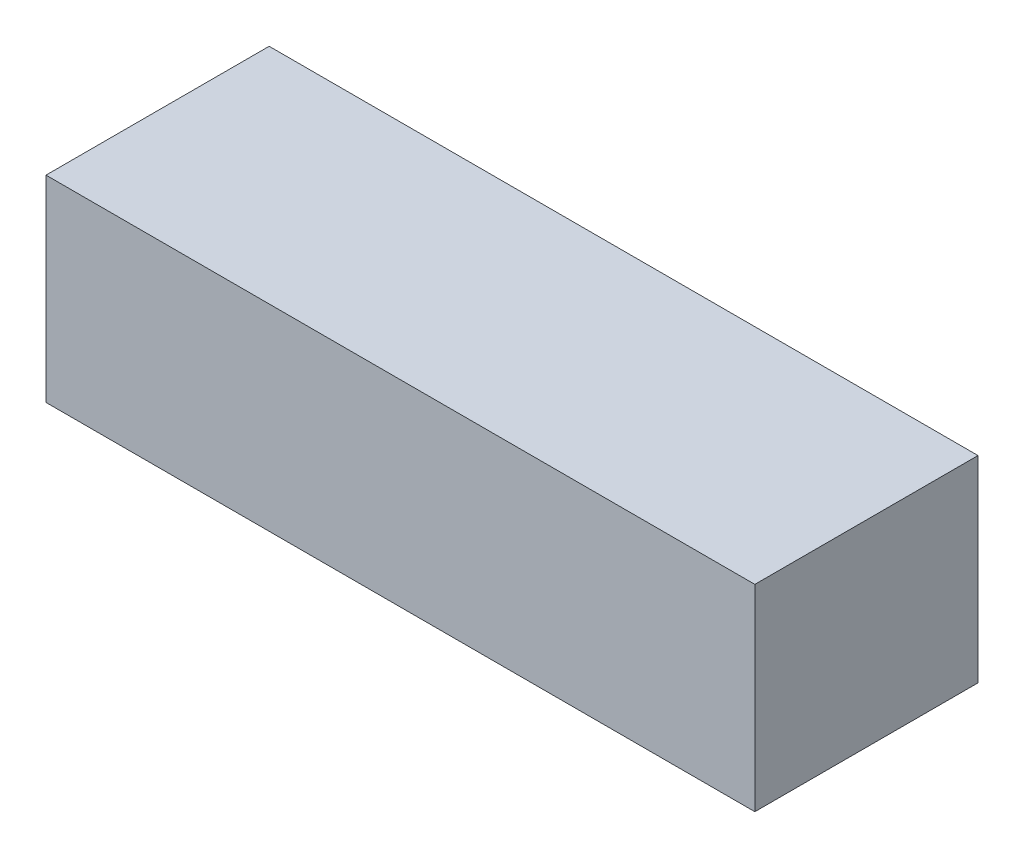
SolidWorks part; units mm, degrees
ref_plane "Front Plane" through (0, 0, 0) normal (0, 0, 1) x (1, 0, 0)
ref_plane "Top Plane" through (0, 0, 0) normal (0, 1, 0) x (1, 0, 0)
ref_plane "Right Plane" through (0, 0, 0) normal (1, 0, 0) x (0, 0, -1)
sketch "Sketch1" plane through (0, 0, 0) normal (0, 1, 0) x (1, 0, 0)
  line L0 (-54, -17) -> (54, -17)
  line L1 (54, -17) -> (54, 17)
  line L2 (54, 17) -> (-54, 17)
  line L3 (-54, 17) -> (-54, -17)
extrude "Boss-Extrude1" add sketch "Sketch1" along normal blind 30
